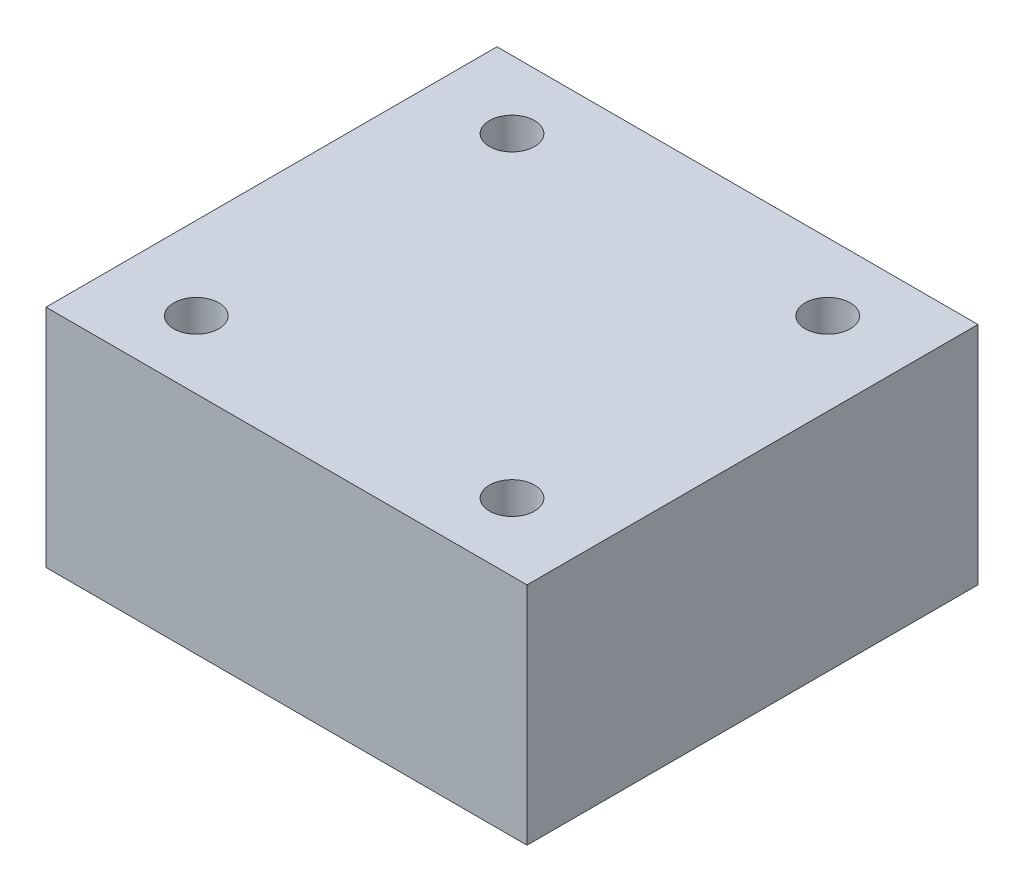
SolidWorks part; units mm, degrees
ref_plane "Front Plane" through (0, 0, 0) normal (0, 0, 1) x (1, 0, 0)
ref_plane "Top Plane" through (0, 0, 0) normal (0, 1, 0) x (1, 0, 0)
ref_plane "Right Plane" through (0, 0, 0) normal (1, 0, 0) x (0, 0, -1)
sketch "Sketch1" plane through (0, 0, 0) normal (0, 1, 0) x (1, 0, 0)
  line L1 (0, 0) -> (32, 0)
  line L2 (0, 0) -> (0, 30)
  line L3 (0, 30) -> (32, 30)
  line L4 (32, 0) -> (32, 30)
  dimension "D1" = 30
  dimension "D2" = 32
extrude "Boss-Extrude1" add sketch "Sketch1" along normal blind 15
sketch "Sketch2" plane through (0, 15, 0) normal (0, 1, 0) x (1, 0, 0)
  line L0 (32, 0) -> (32, 30) construction
  line L1 (7, 6) -> (25, 6)
  line L2 (7, 6) -> (7, 24)
  line L3 (7, 24) -> (25, 24)
  line L4 (25, 6) -> (25, 24)
  line L5 (7, 6) -> (25, 24) construction
  line L6 (7, 24) -> (25, 6) construction
  line L7 (0, 0) -> (32, 0) construction
  line L8 (25, 6) -> (25, 1.1073) construction
  line L9 (25, 6) -> (29.9665, 6) construction
  line L10 (7, 24) -> (7, 28.6679) construction
  line L11 (7, 24) -> (0.9367, 24) construction
  circle A1 centre (26.5, 4.5) radius 1.5
  circle A2 centre (5.5, 4.5) radius 1.5
  circle A4 centre (26.5, 25.5) radius 1.5
  circle A5 centre (5.5, 25.5) radius 1.5
  point P0 (16, 15)
  point P7 (32, 15)
  point P11 (16, 0)
  dimension "D1" = 3
  dimension "D2" = 18
extrude "Cut-Extrude1" cut sketch "Sketch2" against normal blind 15 contours A2 | A5 | A4 | A1
